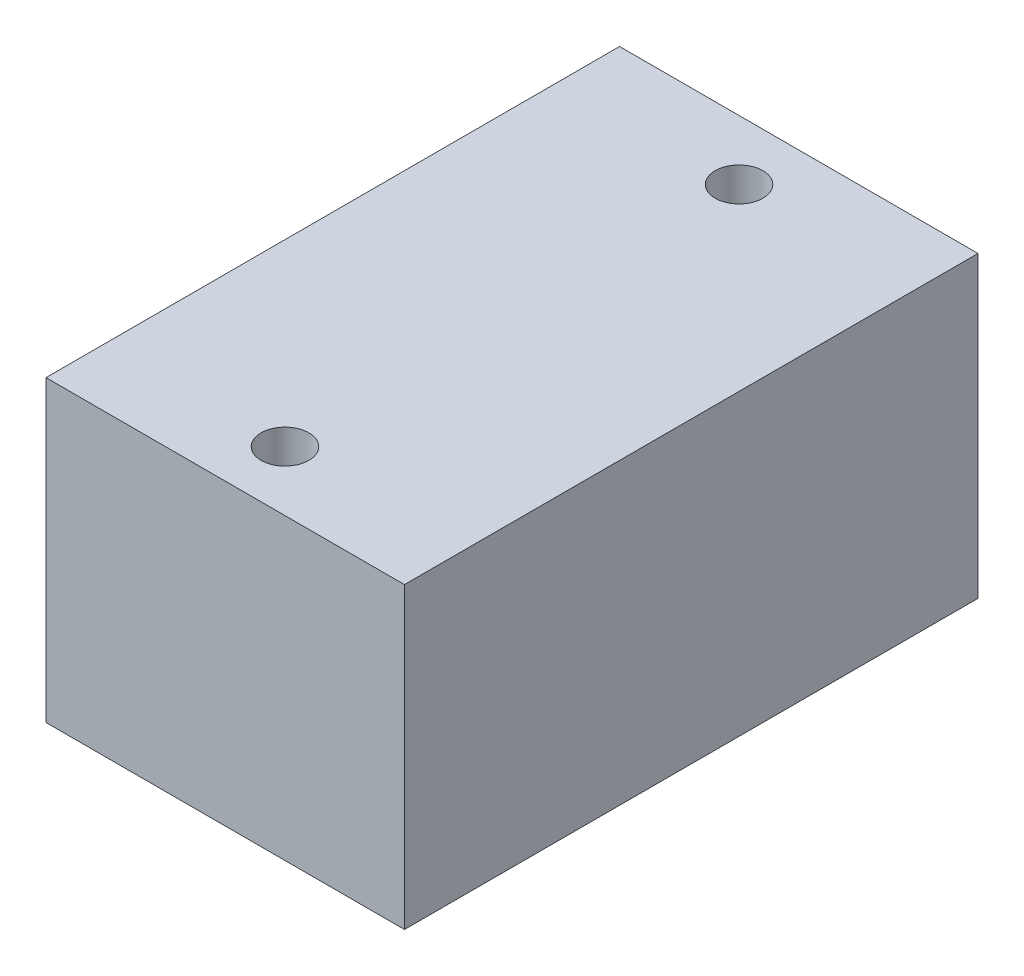
SolidWorks part; units mm, degrees
ref_plane "Front Plane" through (0, 0, 0) normal (0, 0, 1) x (1, 0, 0)
ref_plane "Top Plane" through (0, 0, 0) normal (0, 1, 0) x (1, 0, 0)
ref_plane "Right Plane" through (0, 0, 0) normal (1, 0, 0) x (0, 0, -1)
sketch "Sketch1" plane through (0, 0, 0) normal (0, 0, 1) x (1, 0, 0)
  line L13 (0, 0) -> (30, 0)
  line L14 (0, 0) -> (0, 25)
  line L15 (0, 25) -> (30, 25)
  line L16 (30, 0) -> (30, 25)
  dimension "D1" = 25
  dimension "D2" = 30
extrude "Boss-Extrude1" add sketch "Sketch1" along normal blind 48
sketch "Sketch2" plane through (0, 25, 0) normal (0, 1, 0) x (1, 0, 0)
  line L0 (30, -48) -> (30, 0) construction
  line L1 (30, 0) -> (0, 0) construction
  circle A0 centre (15, -5) radius 2
  circle A1 centre (15, -43) radius 2
  dimension "D1" = 4
  dimension "D2" = 15
  dimension "D3" = 5
  dimension "D4" = 38
extrude "Cut-Extrude3" cut sketch "Sketch2" against normal blind 10
sketch "Sketch3" plane through (0, 0, 0) normal (0, -1, 0) x (1, 0, 0)
  line L0 (0, 48) -> (0, 0) construction
  line L1 (0, 48) -> (30, 48) construction
  circle A0 centre (15, 39) radius 2
  circle A1 centre (15, 9) radius 2
  dimension "D1" = 30
  dimension "D2" = 4
  dimension "D3" = 15
  dimension "D4" = 9
extrude "Cut-Extrude4" cut sketch "Sketch3" against normal blind 10
